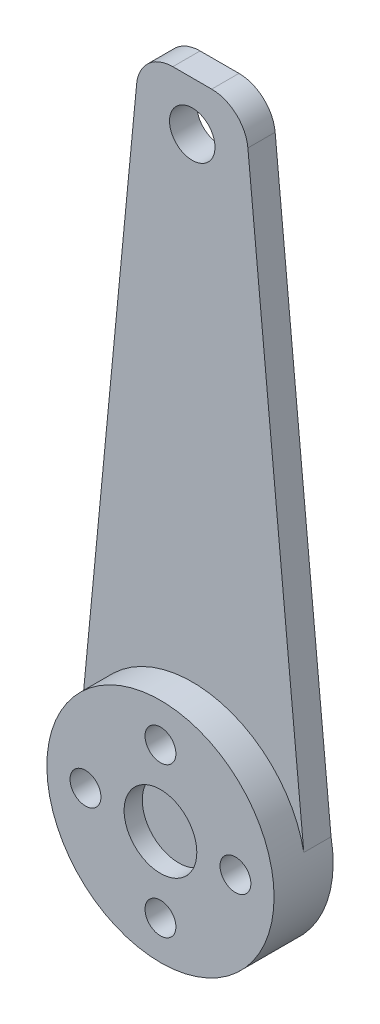
SolidWorks part; units mm, degrees
ref_plane "Plan de face" through (0, 0, 0) normal (0, 0, 1) x (1, 0, 0)
ref_plane "Plan de dessus" through (0, 0, 0) normal (0, 1, 0) x (1, 0, 0)
ref_plane "Plan de droite" through (0, 0, 0) normal (1, 0, 0) x (0, 0, -1)
sketch "Esquisse2" plane through (0, 0, 0) normal (0, 0, 1) x (1, 0, 0)
  circle A0 centre (0, 0) radius 12.5
  circle A1 centre (0, 0) radius 8.25
  dimension "D1" = 25
  dimension "D2" = 16.5
extrude "Boss.-Extru.1" add sketch "Esquisse2" along normal mid plane 6.5 contours A0
sketch "Esquisse3" plane through (0, 0, 0) normal (0, 0, 1) x (1, 0, 0)
  circle A2 centre (0, 8.25) radius 1.2
  circle A3 centre (-8.25, 0) radius 1.2
  circle A4 centre (0, -8.25) radius 1.2
  circle A5 centre (8.25, 0) radius 1.2
  point P3 (-8.25, 0)
  point P11 (0, 8.25)
  point P12 (8.25, 0)
  point P13 (0, -8.25)
  dimension "D1" = 2.4
  dimension "D2" = 2.4
  dimension "D3" = 2.4
  dimension "D4" = 2.4
extrude "Enlèv. mat.-Extru.1" cut sketch "Esquisse3" along normal through all
sketch "Esquisse20" plane through (0, 0, -3.25) normal (0, 0, -1) x (-1, 0, 0)
  line L0 (-12.5, 0) -> (-5.7722, 70.0532)
  line L1 (-5.7722, 70.0532) -> (5.7722, 70.0532)
  line L2 (5.7722, 70.0532) -> (12.5, 0)
  line L3 (12.5, 0) -> (-12.5, 0)
  circle A0 centre (0, 0) radius 12.5 construction
  point P4 (0, 70.0532)
extrude "Boss.-Extru.2" add sketch "Esquisse20" against normal blind 3
sketch "Esquisse10" plane through (0, 0, -3.25) normal (0, 0, -1) x (-1, 0, 0)
  circle A0 centre (-8.25, 0) radius 1.7
  circle A1 centre (0, 8.25) radius 1.7
  circle A2 centre (8.25, 0) radius 1.7
  circle A3 centre (0, -8.25) radius 1.7
  dimension "D1" = 3.4
  dimension "D2" = 3.4
  dimension "D3" = 3.4
  dimension "D4" = 3.4
extrude "Enlèv. mat.-Extru.2" cut sketch "Esquisse10" against normal through all and the other way through all
sketch "Esquisse11" plane through (0, 0, -3.25) normal (0, 0, -1) x (-1, 0, 0)
  line L0 (0, 0) -> (0, -12.5)
  line L1 (0, -12.5) -> (0, 0)
  line L2 (-12.5, 0) -> (0, 0)
  line L3 (0, 0) -> (-8.8388, -8.8388)
  line L4 (-8.8388, -8.8388) -> (8.8388, 8.8388)
  line L5 (-8.8388, -8.8388) -> (-13.3052, -6.8474)
  line L6 (-13.3052, -6.8474) -> (-5.8533, -10.17)
  circle A0 centre (0, 0) radius 12.5 construction
ref_plane "Plan1" through (10.0763, -10.0763, 0) normal (0.7071, -0.7071, 0) x (-0.7071, -0.7071, 0)
sketch "Esquisse13" plane through (10.0763, -10.0763, 0) normal (0.7071, -0.7071, 0) x (-0.7071, -0.7071, 0)
  line L0 (0, 0) -> (0, -3.25)
  line L1 (-12.5, -3.25) -> (12.5, -3.25) construction
  circle A1 centre (0, 0) radius 1
  dimension "D2" = 2
sketch "Esquisse16" plane through (0, 0, 3.25) normal (0, 0, 1) x (1, 0, 0)
  line L0 (0, 0) -> (-6.1179, -5.0018)
sketch "Esquisse17" plane through (0, 0, 3.25) normal (0, 0, 1) x (1, 0, 0)
  circle A0 centre (0, 0) radius 4
  dimension "D1" = 8
extrude "Enlèv. mat.-Extru.8" cut sketch "Esquisse17" against normal blind 2
sketch "Esquisse14" plane through (0, 0, 0) normal (0, 0, 1) x (1, 0, 0)
  circle A0 centre (0, 0) radius 11.75
  circle A1 centre (0, 0) radius 14.25
  dimension "D1" = 23.5
sketch "Esquisse18" plane through (0, 0, 0) normal (0, 1, 0) x (1, 0, 0)
  line L0 (12.5, 2.5) -> (11.0566, 0)
  line L1 (12.5, -3.25) -> (12.5, 3.25) construction
  line L2 (11.0566, 0) -> (12.5, -2.5)
  line L3 (12.5, -2.5) -> (12.5, 2.5)
  line L4 (-14.25, 0) -> (14.25, 0) construction
  line L5 (11.0566, 0) -> (12.5, 0) construction
  point P4 (12.5, 0)
  point P10 (11.0566, 0)
  dimension "D1" = 30
  dimension "D2" = 30
  dimension "D3" = 5
  dimension "D4" = 1.4434
sketch "Esquisse19" plane through (0, 0, 0) normal (1, 0, 0) x (0, 0, -1)
  line L0 (3.25, 0) -> (-5.3209, 0) construction
ref_plane "Plan2" through (9.7351, -8.3209, 0) normal (-0.6497, -0.7602, 0) x (-0.7602, 0.6497, 0)
fillet "Congé1" radius 4 2 edges at (-5.7722, 70.0532, -1.75) (5.7722, 70.0532, -1.75)
sketch "Esquisse21" plane through (0, 0, -3.25) normal (0, 0, -1) x (-1, 0, 0)
  circle A1 centre (0, 64.6965) radius 2.5
  dimension "D1" = 5
extrude "Enlèv. mat.-Extru.9" cut sketch "Esquisse21" against normal through all
